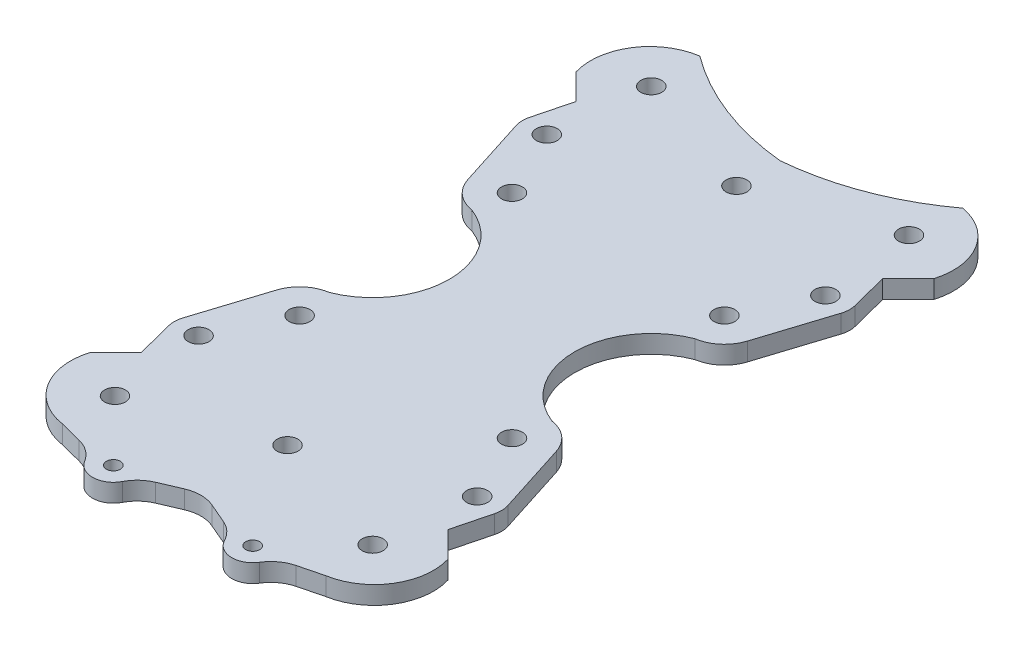
SolidWorks part; units mm, degrees
material "Thornel Mat VMA"
ref_plane "Front Plane" through (0, 0, 0) normal (0, 0, 1) x (1, 0, 0)
ref_plane "Top Plane" through (0, 0, 0) normal (0, 1, 0) x (1, 0, 0)
ref_plane "Right Plane" through (0, 0, 0) normal (1, 0, 0) x (0, 0, -1)
sketch "Sketch1" plane through (0, 0, 0) normal (0, 1, 0) x (1, 0, 0)
  line L0 (123.4756, 1290.8987) -> (175.4725, 1291.4672) construction
  line L1 (167.8436, 1293.6503) -> (130.8436, 1293.6503)
  line L2 (149.3436, 1293.6503) -> (149.3436, 1323.6503) construction
  line L3 (130.5678, 1300.8959) -> (139.0453, 1297.2974)
  line L4 (159.8703, 1297.2612) -> (168.3478, 1300.8597)
  line L7 (123.6486, 1290.0298) -> (131.0005, 1282.6779)
  line L9 (130.8436, 1293.6503) -> (130.8436, 1216.6503) construction
  line L15 (133.3436, 1277.021) -> (133.3436, 1272.6503)
  line L16 (130.8436, 1255.1503) -> (133.3436, 1255.1503) construction
  line L17 (133.3436, 1269.6503) -> (133.3436, 1240.6503)
  line L18 (159.8703, 1213.0394) -> (168.3478, 1209.4409)
  line L19 (130.5678, 1209.4047) -> (139.0453, 1213.0032)
  line L20 (123.6486, 1220.2709) -> (131.0005, 1227.6228)
  line L21 (133.3436, 1233.2796) -> (133.3436, 1237.6503)
  line L22 (175.0387, 1220.2709) -> (167.6868, 1227.6228)
  line L23 (165.3436, 1233.2796) -> (165.3436, 1237.6503)
  line L24 (165.3436, 1269.6503) -> (165.3436, 1240.6503)
  line L25 (165.3436, 1277.021) -> (165.3436, 1272.6503)
  line L26 (175.0387, 1290.0298) -> (167.6868, 1282.6779)
  line L27 (133.3436, 1272.6503) -> (133.3436, 1269.6503)
  line L28 (133.3436, 1240.6503) -> (133.3436, 1237.6503)
  line L29 (165.3436, 1240.6503) -> (165.3436, 1237.6503)
  line L30 (165.3436, 1272.6503) -> (165.3436, 1269.6503)
  circle A0 centre (130.8436, 1293.6503) radius 1.5
  circle A1 centre (167.8436, 1293.6503) radius 1.5
  arc A2 (130.5678, 1300.8959) -> (123.6486, 1290.0298) centre (131.7866, 1292.4838) ccw
  arc A4 (139.0453, 1297.2974) -> (159.8703, 1297.2612) centre (149.4956, 1319.0201) ccw
  arc A5 (175.0387, 1290.0298) -> (168.3478, 1300.8597) centre (166.9007, 1292.4838) ccw
  circle A6 centre (130.8436, 1216.6503) radius 1.5
  circle A7 centre (149.3436, 1287.3814) radius 1.5
  arc A14 (175.0387, 1220.2709) -> (168.3478, 1209.4409) centre (166.9007, 1217.8168) cw
  arc A15 (139.0453, 1213.0032) -> (159.8703, 1213.0394) centre (149.4956, 1191.2805) cw
  arc A17 (130.5678, 1209.4047) -> (123.6486, 1220.2709) centre (131.7866, 1217.8168) cw
  circle A20 centre (149.3436, 1222.9192) radius 1.5
  arc A21 (131.0005, 1227.6228) -> (133.3436, 1233.2796) centre (125.3436, 1233.2796) ccw
  arc A22 (167.6868, 1227.6228) -> (165.3436, 1233.2796) centre (173.3436, 1233.2796) cw
  arc A23 (165.3436, 1277.021) -> (167.6868, 1282.6779) centre (173.3436, 1277.021) cw
  arc A24 (131.0005, 1282.6779) -> (133.3436, 1277.021) centre (125.3436, 1277.021) cw
  circle A25 centre (167.8436, 1216.6503) radius 1.5
  arc A29 (149.3436, 1216.6503) -> (168.3478, 1209.4409) centre (146.0425, 1179.2959) cw
  arc A30 (130.5678, 1209.4047) -> (149.3436, 1216.6503) centre (152.9615, 1179.3252) cw
  arc A31 (149.3436, 1293.6503) -> (168.3478, 1300.8597) centre (146.0425, 1331.0047) ccw
  arc A32 (130.5678, 1300.8959) -> (149.3436, 1293.6503) centre (152.9615, 1330.9754) ccw
  point P54 (133.3436, 1229.9659)
  point P57 (165.3436, 1229.9659)
  point P60 (165.3436, 1280.3347)
  point P63 (133.3436, 1280.3347)
  dimension "D2" = 3
  dimension "D3" = 8
  dimension "D4" = 1.1665
  dimension "D5" = 37
  dimension "D11" = 8.5
  dimension "D13" = 24.1057
  dimension "D20" = 75
  dimension "D19" = 75
  dimension "D1" = 52
  dimension "D6" = 30
  dimension "D7" = 67
  dimension "D8" = 4.3707
  dimension "D9" = 29
  dimension "D10" = 3.6205
  dimension "D12" = 67
  dimension "D14" = 45
  dimension "D15" = 9.2096
  dimension "D16" = 77
  dimension "D18" = 6.2689
  dimension "D22" = 13.7109
extrude "Boss-Extrude1" add sketch "Sketch1" along normal blind 2.6
sketch "Sketch2" plane through (0, 2.6, 0) normal (0, 1, 0) x (1, 0, 0)
  line L0 (171.3627, 1223.9468) -> (172.7334, 1229.2789)
  line L1 (175.0387, 1220.2709) -> (167.6868, 1227.6228) construction
  line L2 (165.3436, 1233.2796) -> (169.3436, 1233.6503)
  line L3 (171.3627, 1223.9468) -> (167.6868, 1227.6228)
  line L4 (149.3436, 1216.6503) -> (149.3436, 1222.9192) construction
  line L5 (127.3246, 1223.9468) -> (131.0005, 1227.6228)
  line L6 (133.3436, 1233.2796) -> (129.3436, 1233.6503)
  line L7 (127.3246, 1223.9468) -> (125.9539, 1229.2789)
  line L8 (133.3436, 1255.1503) -> (165.3436, 1255.1503) construction
  line L9 (133.3436, 1277.021) -> (133.3436, 1233.2796) construction
  line L10 (165.3436, 1277.021) -> (165.3436, 1233.2796) construction
  line L11 (171.3627, 1286.3538) -> (172.7334, 1281.0217)
  line L12 (171.3627, 1286.3538) -> (167.6868, 1282.6779)
  line L13 (165.3436, 1277.021) -> (169.3436, 1276.6503)
  line L14 (127.3246, 1286.3538) -> (125.9539, 1281.0217)
  line L15 (133.3436, 1277.021) -> (129.3436, 1276.6503)
  line L16 (127.3246, 1286.3538) -> (131.0005, 1282.6779)
  circle A0 centre (169.3436, 1230.1503) radius 1.5
  circle A1 centre (167.8436, 1216.6503) radius 1.5 construction
  arc A2 (172.7334, 1229.2789) -> (169.3436, 1233.6503) centre (169.3436, 1230.1503) ccw
  arc A3 (165.3436, 1233.2796) -> (167.6868, 1227.6228) centre (173.3436, 1233.2796) ccw construction
  arc A4 (165.3436, 1233.2796) -> (167.6868, 1227.6228) centre (173.3436, 1233.2796) ccw
  arc A5 (133.3436, 1233.2796) -> (131.0005, 1227.6228) centre (125.3436, 1233.2796) cw
  circle A6 centre (129.3436, 1230.1503) radius 1.5
  arc A7 (125.9539, 1229.2789) -> (129.3436, 1233.6503) centre (129.3436, 1230.1503) cw
  circle A8 centre (169.3436, 1280.1503) radius 1.5
  arc A9 (165.3436, 1277.021) -> (167.6868, 1282.6779) centre (173.3436, 1277.021) cw
  arc A10 (172.7334, 1281.0217) -> (169.3436, 1276.6503) centre (169.3436, 1280.1503) cw
  circle A11 centre (129.3436, 1280.1503) radius 1.5
  arc A12 (125.9539, 1281.0217) -> (129.3436, 1276.6503) centre (129.3436, 1280.1503) ccw
  arc A13 (133.3436, 1277.021) -> (131.0005, 1282.6779) centre (125.3436, 1277.021) ccw
  dimension "D1" = 50
  dimension "D3" = 2
  dimension "D2" = 40
extrude "Boss-Extrude2" add sketch "Sketch2" against normal up to surface (2.6 mm away) up to face at (149.3634, 0, -1255.1503)
sketch "Sketch3" plane through (0, 2.6, 0) normal (0, 1, 0) x (1, 0, 0)
  line L0 (133.3436, 1255.1503) -> (165.3436, 1255.1503) construction
  line L1 (133.3436, 1277.021) -> (133.3436, 1233.2796) construction
  line L2 (165.3436, 1233.2796) -> (165.3436, 1277.021) construction
  line L3 (149.3436, 1287.3814) -> (149.3436, 1222.9192) construction
  line L4 (134.0936, 1239.9003) -> (164.5936, 1239.9003) construction
  line L5 (144.3436, 1239.9003) -> (144.3436, 1270.4003) construction
  circle A2 centre (134.0936, 1239.9003) radius 1.5
  circle A3 centre (164.5936, 1239.9003) radius 1.5
  circle A4 centre (164.5936, 1270.4003) radius 1.5
  circle A5 centre (134.0936, 1270.4003) radius 1.5
  circle A6 centre (129.3436, 1230.1503) radius 1.5 construction
  circle A7 centre (169.3436, 1255.1503) radius 11
  circle A9 centre (129.3436, 1255.1503) radius 11
  point P17 (149.3436, 1239.9003)
  point P18 (144.3436, 1255.1503)
  dimension "D3" = 22
  dimension "D1" = 30.5
  dimension "D2" = 30.5
  dimension "D4" = 20
  dimension "D5" = 5
extrude "Cut-Extrude2" cut sketch "Sketch3" against normal up to surface (2.6 mm away) up to face at (149.3574, 0, -1255.1503)
sketch "Sketch4" plane through (0, 2.6, 0) normal (0, 1, 0) x (1, 0, 0)
  line L0 (149.3436, 1222.9192) -> (149.3436, 1287.3814) construction
  line L1 (149.3436, 1255.1503) -> (151.3436, 1255.1503) construction
  line L2 (172.6778, 1231.215) -> (169.4128, 1241.4392)
  line L3 (169.3436, 1233.6503) -> (165.3436, 1233.2796) construction
  line L4 (165.3436, 1233.2796) -> (165.3436, 1238.6013) construction
  line L5 (169.3436, 1233.6503) -> (165.3436, 1233.2796)
  line L6 (165.3436, 1233.2796) -> (165.3436, 1234.8973)
  line L7 (129.3436, 1233.6503) -> (133.3436, 1233.2796)
  line L8 (133.3436, 1233.2796) -> (133.3436, 1234.8973)
  line L9 (126.0095, 1231.215) -> (129.2744, 1241.4392)
  line L10 (172.6778, 1279.0856) -> (169.4128, 1268.8614)
  line L11 (169.3436, 1276.6503) -> (165.3436, 1277.021)
  line L12 (165.3436, 1277.021) -> (165.3436, 1275.4034)
  line L13 (126.0095, 1279.0856) -> (129.2744, 1268.8614)
  line L14 (133.3436, 1277.021) -> (133.3436, 1275.4034)
  line L15 (129.3436, 1276.6503) -> (133.3436, 1277.021)
  arc A0 (169.4128, 1241.4392) -> (165.3436, 1234.8973) centre (164.5936, 1239.9003) ccw
  arc A1 (172.7334, 1229.2789) -> (169.3436, 1233.6503) centre (169.3436, 1230.1503) ccw construction
  circle A4 centre (164.5936, 1239.9003) radius 1.5
  circle A5 centre (169.3436, 1230.1503) radius 1.5 construction
  arc A10 (172.6778, 1231.215) -> (169.3436, 1233.6503) centre (169.3436, 1230.1503) ccw
  arc A11 (126.0095, 1231.215) -> (129.3436, 1233.6503) centre (129.3436, 1230.1503) cw
  circle A12 centre (134.0936, 1239.9003) radius 1.5
  arc A13 (129.2744, 1241.4392) -> (133.3436, 1234.8973) centre (134.0936, 1239.9003) cw
  circle A14 centre (164.5936, 1270.4003) radius 1.5
  circle A15 centre (134.0936, 1270.4003) radius 1.5
  arc A16 (172.6778, 1279.0856) -> (169.3436, 1276.6503) centre (169.3436, 1280.1503) cw
  arc A17 (169.4128, 1268.8614) -> (165.3436, 1275.4034) centre (164.5936, 1270.4003) cw
  arc A18 (129.2744, 1268.8614) -> (133.3436, 1275.4034) centre (134.0936, 1270.4003) ccw
  arc A19 (126.0095, 1279.0856) -> (129.3436, 1276.6503) centre (129.3436, 1280.1503) ccw
  dimension "D1" = 2
extrude "Boss-Extrude3" add sketch "Sketch4" against normal up to surface (2.6 mm away) up to face at (149.353, 0, -1255.1503)
sketch "Sketch5" plane through (0, 2.6, 0) normal (0, 1, 0) x (1, 0, 0)
  line L4 (149.3436, 1216.6503) -> (149.3436, 1207.9192) construction
  line L5 (139.3436, 1207.9192) -> (149.3436, 1207.9192) construction
  line L6 (149.3436, 1207.9192) -> (159.3436, 1207.9192) construction
  line L7 (168.3478, 1209.4409) -> (162.3436, 1207.9192)
  line L8 (130.5678, 1209.4047) -> (136.3436, 1207.9192)
  line L9 (142.3436, 1207.9192) -> (149.3436, 1210.9192)
  line L10 (149.3436, 1210.9192) -> (156.3436, 1207.9192)
  circle A2 centre (139.3436, 1207.9192) radius 1
  circle A3 centre (159.3436, 1207.9192) radius 1
  circle A4 centre (149.3436, 1222.9192) radius 1.5 construction
  arc A5 (136.3436, 1207.9192) -> (142.3436, 1207.9192) centre (139.3436, 1207.9192) ccw
  arc A6 (156.3436, 1207.9192) -> (162.3436, 1207.9192) centre (159.3436, 1207.9192) ccw
  arc A7 (168.3478, 1209.4409) -> (149.3436, 1216.6503) centre (146.0425, 1179.2959) ccw construction
  arc A8 (149.3436, 1216.6503) -> (130.5678, 1209.4047) centre (152.9615, 1179.3252) ccw construction
  arc A9 (168.3478, 1209.4409) -> (149.3436, 1216.6503) centre (146.0425, 1179.2959) ccw
  arc A10 (149.3436, 1216.6503) -> (130.5678, 1209.4047) centre (152.9615, 1179.3252) ccw
  dimension "D2" = 2
  dimension "D3" = 15
  dimension "D4" = 2
  dimension "D1" = 20
  dimension "D5" = 3
extrude "Boss-Extrude5" add sketch "Sketch5" against normal up to surface (2.6 mm away) up to face at (134.0936, 0, -1268.9003)
fillet "Fillet1" radius 5 5 edges at (149.3436, 1.3, -1210.9192) (156.3436, 1.3, -1207.9192) (162.3436, 1.3, -1207.9192) (142.3436, 1.3, -1207.9192) (136.3436, 1.3, -1207.9192)
ref_plane "Plane1" through (149.3436, 0, 0) normal (1, 0, 0) x (0, 0, -1)
ref_plane "Plane2" through (0, 0, -1255.1503) normal (0, 0, 1) x (1, 0, 0)
